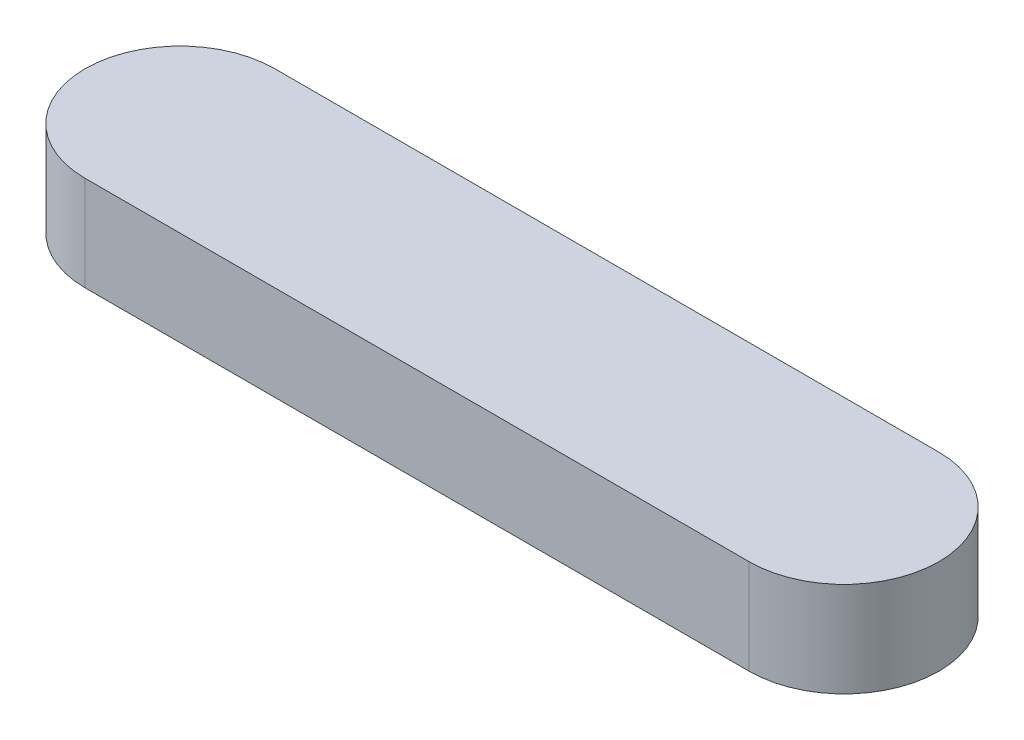
SolidWorks part; units mm, degrees
ref_plane "Front Plane" through (0, 0, 0) normal (0, 0, 1) x (1, 0, 0)
ref_plane "Top Plane" through (0, 0, 0) normal (0, 1, 0) x (1, 0, 0)
ref_plane "Right Plane" through (0, 0, 0) normal (1, 0, 0) x (0, 0, -1)
sketch "Sketch1" plane through (0, 0, 0) normal (0, 1, 0) x (1, 0, 0)
  line L0 (-114.3, 25.4) -> (63.5, 25.4)
  line L1 (-114.3, -25.4) -> (63.5, -25.4)
  line L2 (-114.3, 25.4) -> (-114.3, -25.4) construction
  line L3 (63.5, 25.4) -> (63.5, -25.4) construction
  arc A0 (63.5, 25.4) -> (63.5, -25.4) centre (63.5, 0) cw
  arc A1 (-114.3, 25.4) -> (-114.3, -25.4) centre (-114.3, 0) ccw
  point P3 (-25.4, 25.4)
  dimension "D1" = 177.8
  dimension "D2" = 25.4
  dimension "D3" = 50.8
  dimension "D4" = 63.5
extrude "Boss-Extrude1" add sketch "Sketch1" along normal blind 25.4
